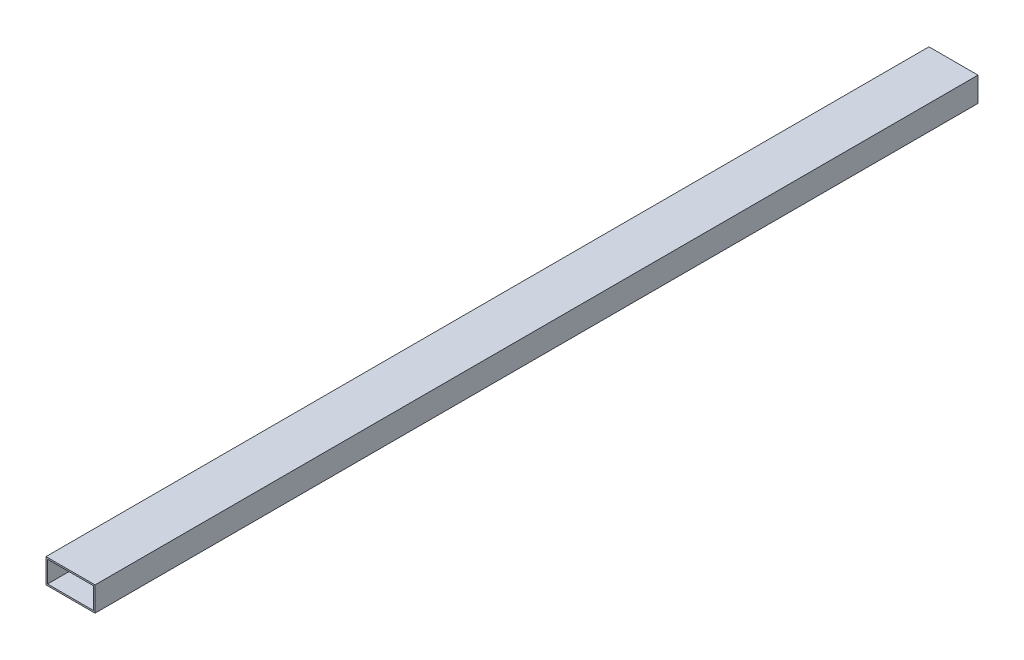
SolidWorks part; units mm, degrees
ref_plane "Front Plane" through (0, 0, 0) normal (0, 0, 1) x (1, 0, 0)
ref_plane "Top Plane" through (0, 0, 0) normal (0, 1, 0) x (1, 0, 0)
ref_plane "Right Plane" through (0, 0, 0) normal (1, 0, 0) x (0, 0, -1)
sketch "Sketch1" plane through (0, 0, 0) normal (0, 0, 1) x (1, 0, 0)
  line L0 (-23.8125, 11.1125) -> (23.8125, 11.1125)
  line L2 (-25.4, 12.7) -> (25.4, 12.7)
  line L3 (-25.4, 12.7) -> (-25.4, -12.7)
  line L4 (-25.4, -12.7) -> (25.4, -12.7)
  line L5 (25.4, 12.7) -> (25.4, -12.7)
  line L10 (23.8125, 11.1125) -> (23.8125, -11.1125)
  line L11 (-23.8125, -11.1125) -> (23.8125, -11.1125)
  line L12 (-23.8125, 11.1125) -> (-23.8125, -11.1125)
  point P12 (0, 12.7)
  point P14 (25.4, 0)
  dimension "Wall Thickness" = 1.5875
  dimension "Outside Width" = 50.8
  dimension "Outside Height" = 25.4
  dimension "Inside Height" = 22.225
  dimension "Inside Width" = 47.625
sketch "Sketch2" plane through (0, 0, 0) normal (1, 0, 0) x (0, 0, -1)
  line L0 (457.2, 0) -> (-457.2, 0)
  point P4 (0, 0)
  point P7 (-457.2, 0)
  point P10 (457.2, 0)
  dimension "Length" = 914.4
sketch "Sketch3" plane through (0, 0, 0) normal (0, 0, 1) x (1, 0, 0)
  line L21 (25.4, 12.7) -> (-25.4, 12.7)
  line L22 (25.4, -12.7) -> (25.4, 12.7)
  line L23 (-25.4, -12.7) -> (25.4, -12.7)
  line L24 (-25.4, 12.7) -> (-25.4, -12.7)
  line L25 (25.4, 12.7) -> (-25.4, 12.7)
  line L26 (25.4, -12.7) -> (25.4, 12.7)
  line L27 (-25.4, -12.7) -> (25.4, -12.7)
  line L28 (-25.4, 12.7) -> (-25.4, -12.7)
  line L29 (23.8125, 11.1125) -> (-23.8125, 11.1125)
  line L30 (23.8125, -11.1125) -> (23.8125, 11.1125)
  line L31 (-23.8125, -11.1125) -> (23.8125, -11.1125)
  line L32 (-23.8125, 11.1125) -> (-23.8125, -11.1125)
  line L33 (23.8125, 11.1125) -> (-23.8125, 11.1125)
  line L34 (23.8125, -11.1125) -> (23.8125, 11.1125)
  line L35 (-23.8125, -11.1125) -> (23.8125, -11.1125)
  line L36 (-23.8125, 11.1125) -> (-23.8125, -11.1125)
  dimension "D1" = 0
  dimension "D2" = 0
extrude "Boss-Extrude1" add sketch "Sketch3" along normal up to vertex (457.2 mm away) and the other way up to vertex (457.2 mm away) up to point (0, 0, 457.2) other way up to point (0, 0, -457.2)
sketch "Drawing Reference" plane through (0, 0, 0) normal (1, 0, 0) x (0, 0, -1)
  line L0 (-457.2, 0) -> (457.2, 0) construction
  line L1 (0, -12.7) -> (0, 12.7) construction
  line L2 (-457.2, -12.7) -> (457.2, -12.7) construction
  line L5 (-457.2, 12.7) -> (457.2, 12.7) construction
  point P7 (-420.624, 0)
  point P8 (420.624, 0)
  dimension "D1" = 36.576
equation "\"D1@Drawing Reference\"=\"Outside Width@Sketch1\" * 0.72"
